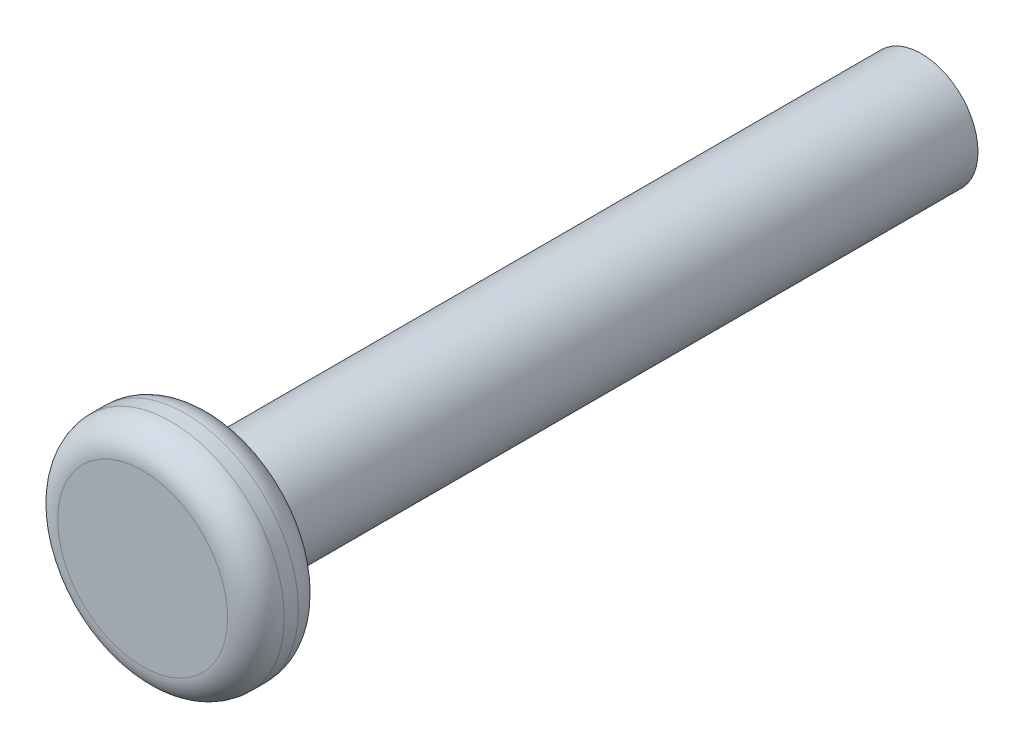
SolidWorks part; units mm, degrees
ref_plane "Front Plane" through (0, 0, 0) normal (0, 0, 1) x (1, 0, 0)
ref_plane "Top Plane" through (0, 0, 0) normal (0, 1, 0) x (1, 0, 0)
ref_plane "Right Plane" through (0, 0, 0) normal (1, 0, 0) x (0, 0, -1)
sketch "Sketch1" plane through (0, 0, 0) normal (0, 0, 1) x (1, 0, 0)
  circle A0 centre (0, 0) radius 4
  dimension "D1" = 8
extrude "Boss-Extrude1" add sketch "Sketch1" along normal blind 50
sketch "Sketch2" plane through (0, 0, 50) normal (0, 0, 1) x (1, 0, 0)
  circle A0 centre (0, 0) radius 8
  dimension "D1" = 16
extrude "Boss-Extrude2" add sketch "Sketch2" along normal blind 5
fillet "Fillet2" radius 2 2 edges at (8, 0, 50) (8, 0, 55)
